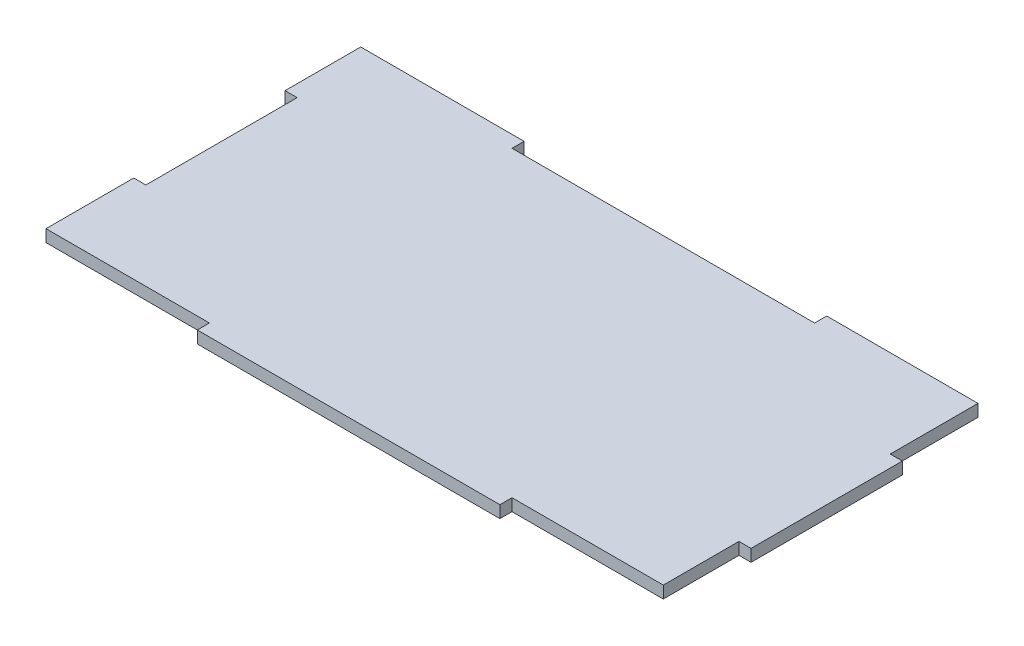
SolidWorks part; units mm, degrees
ref_plane "Front Plane" through (0, 0, 0) normal (0, 0, 1) x (1, 0, 0)
ref_plane "Top Plane" through (0, 0, 0) normal (0, 1, 0) x (1, 0, 0)
ref_plane "Right Plane" through (0, 0, 0) normal (1, 0, 0) x (0, 0, -1)
sketch "Sketch1" plane through (0, 0, 0) normal (0, 1, 0) x (1, 0, 0)
  line L0 (-65.7389, 40.2513) -> (-65.7389, 44.2513)
  line L1 (-65.7389, 44.2513) -> (-119.7389, 44.2513)
  line L2 (-119.7389, 44.2513) -> (-119.7389, 19.2513)
  line L3 (-119.7389, 19.2513) -> (-115.7389, 19.2513)
  line L4 (-115.7389, 19.2513) -> (-115.7389, -30.7487)
  line L5 (-115.7389, -30.7487) -> (-119.7389, -30.7487)
  line L6 (-119.7389, -30.7487) -> (-119.7389, -59.7487)
  line L7 (-119.7389, -59.7487) -> (-115.7389, -59.7487)
  line L8 (-115.7389, -59.7487) -> (-65.7389, -59.7487)
  line L9 (-65.7389, -59.7487) -> (-65.7389, -63.7487)
  line L10 (-65.7389, -63.7487) -> (34.2611, -63.7487)
  line L11 (34.2611, -63.7487) -> (34.2611, -59.7487)
  line L12 (34.2611, -59.7487) -> (84.2611, -59.7487)
  line L13 (84.2611, -59.7487) -> (84.2611, -34.7487)
  line L14 (84.2611, -34.7487) -> (88.2611, -34.7487)
  line L15 (88.2611, -34.7487) -> (88.2611, 15.2513)
  line L16 (88.2611, 15.2513) -> (84.2611, 15.2513)
  line L17 (84.2611, 15.2513) -> (84.2611, 44.2513)
  line L18 (84.2611, 44.2513) -> (34.2611, 44.2513)
  line L19 (34.2611, 44.2513) -> (34.2611, 40.2513)
  line L20 (34.2611, 40.2513) -> (-65.7389, 40.2513)
extrude "Boss-Extrude1" add sketch "Sketch1" along normal blind 4
